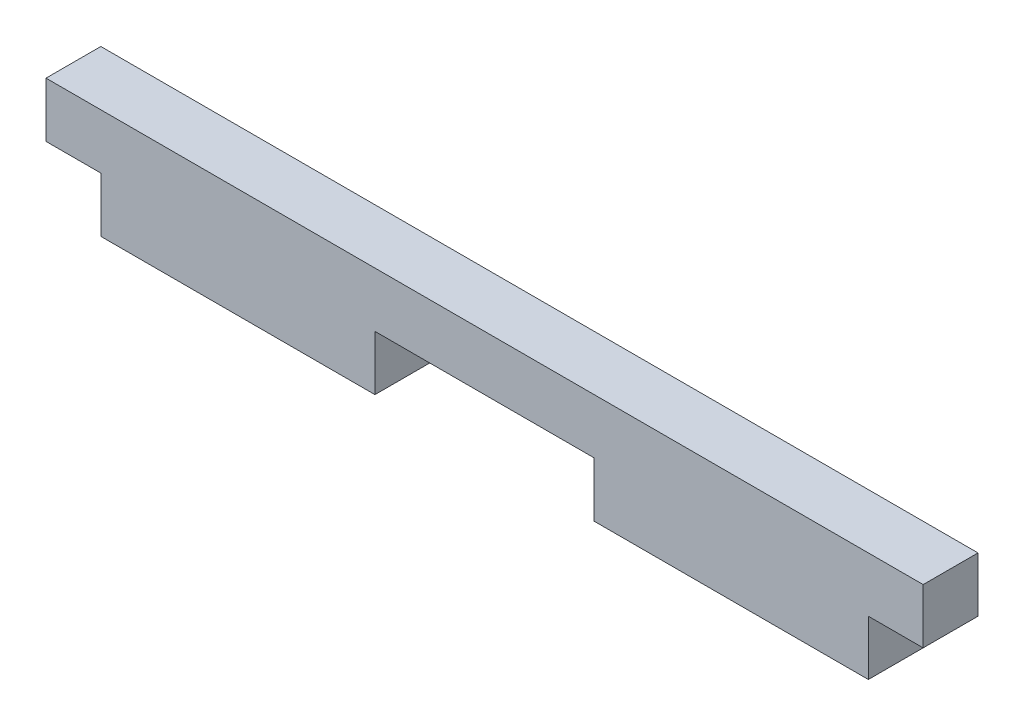
SolidWorks part; units mm, degrees
ref_plane "Спереди" through (0, 0, 0) normal (0, 0, 1) x (1, 0, 0)
ref_plane "Сверху" through (0, 0, 0) normal (0, 1, 0) x (1, 0, 0)
ref_plane "Справа" through (0, 0, 0) normal (1, 0, 0) x (0, 0, -1)
sketch "Sketch1" plane through (0, 0, 0) normal (0, 0, 1) x (1, 0, 0)
  line L0 (40, 5) -> (40, -3.691) construction
  line L1 (0, 0) -> (5, 0)
  line L2 (0, 0) -> (0, 5)
  line L3 (0, 5) -> (80, 5)
  line L4 (80, 0) -> (80, 5)
  line L6 (5, 0) -> (5, -5)
  line L7 (5, -5) -> (30, -5)
  line L8 (30, 0) -> (30, -5)
  line L9 (30, 0) -> (50, 0)
  line L10 (75, 0) -> (75, -5)
  line L11 (75, -5) -> (50, -5)
  line L12 (50, 0) -> (50, -5)
  line L13 (75, 0) -> (80, 0)
  dimension "D1" = 80
  dimension "D2" = 5
  dimension "D3" = 5
  dimension "D4" = 5
  dimension "D5" = 25
extrude "Boss-Extrude1" add sketch "Sketch1" along normal blind 5
